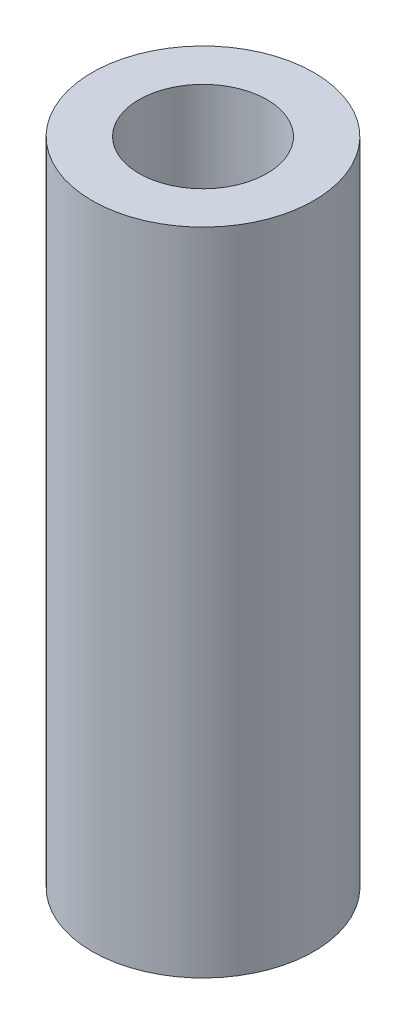
SolidWorks part; units mm, degrees
ref_plane "Front Plane" through (0, 0, 0) normal (0, 0, 1) x (1, 0, 0)
ref_plane "Top Plane" through (0, 0, 0) normal (0, 1, 0) x (1, 0, 0)
ref_plane "Right Plane" through (0, 0, 0) normal (1, 0, 0) x (0, 0, -1)
sketch "Sketch1" plane through (0, 0, 0) normal (0, 1, 0) x (1, 0, 0)
  circle A0 centre (0, 0) radius 1.875
  circle A1 centre (0, 0) radius 3.25
  dimension "D1" = 3.75
  dimension "D2" = 6.5
extrude "Boss-Extrude1" add sketch "Sketch1" along normal blind 19.05
